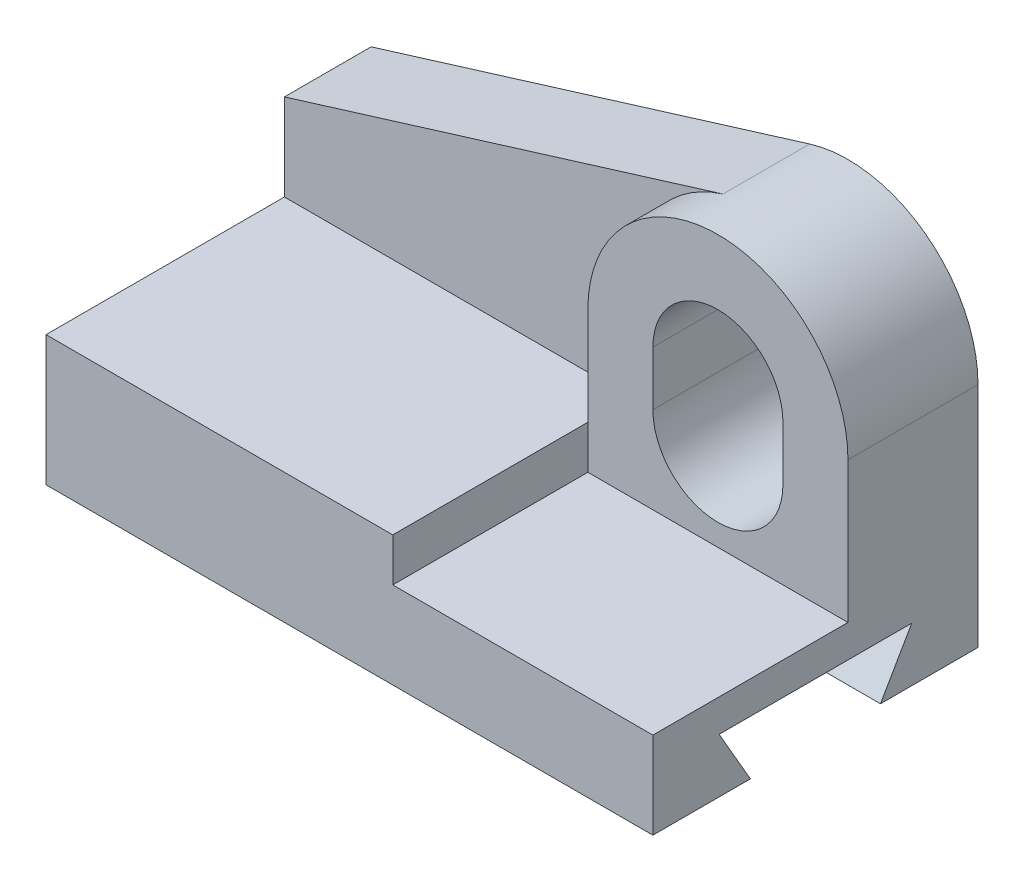
SolidWorks part; units mm, degrees
ref_plane "前视基准面" through (0, 0, 0) normal (0, 0, 1) x (1, 0, 0)
ref_plane "上视基准面" through (0, 0, 0) normal (0, 1, 0) x (1, 0, 0)
ref_plane "右视基准面" through (0, 0, 0) normal (1, 0, 0) x (0, 0, -1)
other "Configuration Table"
sketch "草图1" plane through (0, 0, 0) normal (0, 1, 0) x (1, 0, 0)
  line L1 (-28, -15) -> (28, -15)
  line L2 (-28, -15) -> (-28, 15)
  line L3 (-28, 15) -> (28, 15)
  line L4 (28, -15) -> (28, 15)
  line L5 (0, 15) -> (0, -15) construction
  line L6 (-28, 0) -> (28, 0) construction
  point P0 (0, 0)
  dimension "D1" = 56
  dimension "D2" = 30
extrude "凸台-拉伸1" add sketch "草图1" along normal blind 8
sketch "草图2" plane through (0, 8, 0) normal (0, 1, 0) x (1, 0, 0)
  line L0 (-28, -15) -> (4, -15)
  line L1 (-28, -15) -> (28, -15) construction
  line L2 (4, -15) -> (4, 15)
  line L3 (28, 15) -> (-28, 15) construction
  line L4 (4, 15) -> (-28, 15)
  line L5 (-28, 15) -> (-28, -15) construction
  line L6 (-28, 15) -> (-28, -15)
  dimension "D1" = 32
extrude "凸台-拉伸2" add sketch "草图2" along normal blind 4
sketch "草图3" plane through (-28, 0, 0) normal (-1, 0, 0) x (0, 0, 1)
  line L0 (-6, 0) -> (6, 0)
  line L1 (-15, 0) -> (15, 0) construction
  line L2 (6, 0) -> (8.8868, 5)
  line L3 (8.8868, 5) -> (-8.8868, 5)
  line L4 (-8.8868, 5) -> (-6, 0)
  line L5 (0, 0) -> (0, 12) construction
  line L6 (-15, 12) -> (15, 12) construction
  point P11 (0, 5)
  dimension "D1" = 12
  dimension "D2" = 60
  dimension "D3" = 5
extrude "切除-拉伸1" cut sketch "草图3" against normal through all
ref_plane "基准面1" through (0, 0, -15) normal (0, 0, 1) x (1, 0, 0)
sketch "草图4" plane through (0, 0, -15) normal (0, 0, 1) x (1, 0, 0)
  line L0 (28, 8) -> (28, 21)
  line L1 (4, 8) -> (4, 21)
  line L2 (4, 8) -> (28, 8)
  line L3 (16, 8) -> (16, 33.5472) construction
  line L4 (4, 21) -> (28, 21) construction
  line L5 (10, 21) -> (10, 16)
  line L6 (22, 21) -> (22, 16)
  line L7 (10, 16) -> (22, 16) construction
  arc A0 (4, 21) -> (28, 21) centre (16, 21) cw
  arc A1 (10, 21) -> (22, 21) centre (16, 21) cw
  arc A2 (10, 16) -> (22, 16) centre (16, 16) ccw
  dimension "D1" = 5
  dimension "D3" = 6
  dimension "D2" = 8
extrude "凸台-拉伸3" add sketch "草图4" along normal blind 12
sketch "草图5" plane through (0, 0, -15) normal (0, 0, 1) x (1, 0, 0)
  line L0 (-28, 12) -> (-28, 20)
  line L1 (-28, 20) -> (12.4666, 32.468)
  line L2 (-28, 12) -> (4, 12)
  line L3 (4, 12) -> (4, 21)
  arc A0 (28, 21) -> (4, 21) centre (16, 21) ccw construction
  arc A1 (12.4666, 32.468) -> (4, 21) centre (16, 21) ccw
  dimension "D1" = 8
extrude "凸台-拉伸4" add sketch "草图5" along normal blind 8
